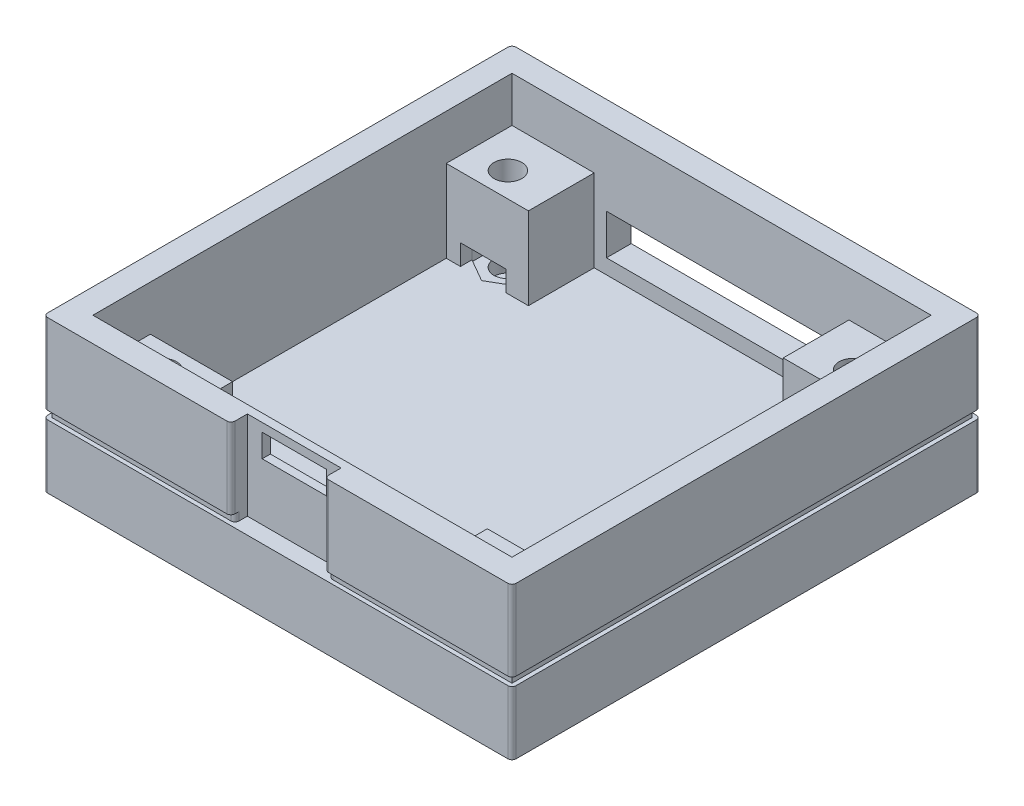
SolidWorks part; units mm, degrees
ref_plane "Plan de face" through (0, 0, 0) normal (0, 0, 1) x (1, 0, 0)
ref_plane "Plan de dessus" through (0, 0, 0) normal (0, 1, 0) x (1, 0, 0)
ref_plane "Plan de droite" through (0, 0, 0) normal (1, 0, 0) x (0, 0, -1)
sketch "Esquisse1" plane through (0, 0, 0) normal (0, 1, 0) x (1, 0, 0)
  line L1 (-30.0101, 36.8942) -> (26.9899, 36.8942)
  line L2 (-30.0101, 36.8942) -> (-30.0101, -20.1058)
  line L3 (-30.0101, -20.1058) -> (26.9899, -20.1058)
  line L4 (26.9899, 36.8942) -> (26.9899, -20.1058)
extrude "Boss.-Extru.1" add sketch "Esquisse1" along normal blind 18.5 contours L2 L3 L4 L1
sketch "Esquisse2" plane through (0, 18.5, 0) normal (0, 1, 0) x (1, 0, 0)
  line L0 (-30.0101, 36.8942) -> (26.9899, 36.8942) construction
  line L1 (-27.0101, 33.8942) -> (23.9899, 33.8942)
  line L2 (-27.0101, 33.8942) -> (-27.0101, -17.1058)
  line L3 (-27.0101, -17.1058) -> (23.9899, -17.1058)
  line L4 (23.9899, 33.8942) -> (23.9899, -17.1058)
  line L5 (-30.0101, 36.8942) -> (-30.0101, -20.1058) construction
  line L6 (26.9899, 36.8942) -> (26.9899, -20.1058) construction
  line L7 (-30.0101, -20.1058) -> (26.9899, -20.1058) construction
  dimension "D1" = 3
  dimension "D2" = 3
  dimension "D3" = 3
  dimension "D4" = 3
extrude "Enlèv. mat.-Extru.1" cut sketch "Esquisse2" against normal blind 15.5 contours L2 L3 L4 L1
sketch "Esquisse4" plane through (0, 3, 0) normal (0, 1, 0) x (1, 0, 0)
  line L1 (-17.0101, 25.8942) -> (-27.0101, 25.8942)
  line L2 (-17.0101, 25.8942) -> (-17.0101, 33.8942)
  line L3 (-17.0101, 33.8942) -> (-27.0101, 33.8942)
  line L4 (-27.0101, 25.8942) -> (-27.0101, 33.8942)
extrude "Boss.-Extru.2" add sketch "Esquisse4" along normal blind 10
sketch "Esquisse5" plane through (0, 3, 0) normal (0, 1, 0) x (1, 0, 0)
  line L1 (23.9899, 33.8942) -> (13.9899, 33.8942)
  line L2 (23.9899, 33.8942) -> (23.9899, 25.8942)
  line L3 (23.9899, 25.8942) -> (13.9899, 25.8942)
  line L4 (13.9899, 33.8942) -> (13.9899, 25.8942)
extrude "Boss.-Extru.3" add sketch "Esquisse5" along normal blind 10
sketch "Esquisse6" plane through (0, 3, 0) normal (0, 1, 0) x (1, 0, 0)
  line L1 (23.9899, -17.1058) -> (13.9899, -17.1058)
  line L2 (23.9899, -17.1058) -> (23.9899, -10.1058)
  line L3 (23.9899, -10.1058) -> (13.9899, -10.1058)
  line L4 (13.9899, -17.1058) -> (13.9899, -10.1058)
extrude "Boss.-Extru.4" add sketch "Esquisse6" along normal blind 10
sketch "Esquisse7" plane through (0, 3, 0) normal (0, 1, 0) x (1, 0, 0)
  line L1 (-17.0101, -10.1058) -> (-27.0101, -10.1058)
  line L2 (-17.0101, -10.1058) -> (-17.0101, -17.1058)
  line L3 (-17.0101, -17.1058) -> (-27.0101, -17.1058)
  line L4 (-27.0101, -10.1058) -> (-27.0101, -17.1058)
extrude "Boss.-Extru.5" add sketch "Esquisse7" along normal blind 10
sketch "Esquisse8" plane through (0, 13, 0) normal (0, 1, 0) x (1, 0, 0)
  line L0 (13.9899, -17.1058) -> (23.9899, -17.1058) construction
  line L2 (23.9899, -17.1058) -> (23.9899, -10.1058) construction
  circle A0 centre (19.4899, -13.1058) radius 1.7
  dimension "D1" = 4
  dimension "D2" = 4.5
extrude "Enlèv. mat.-Extru.2" cut sketch "Esquisse8" against normal blind 12
sketch "Esquisse9" plane through (0, 13, 0) normal (0, 1, 0) x (1, 0, 0)
  line L0 (-27.0101, -17.1058) -> (-17.0101, -17.1058) construction
  line L1 (-27.0101, -10.1058) -> (-27.0101, -17.1058) construction
  circle A0 centre (-22.5101, -13.1058) radius 1.7
  dimension "D1" = 4
  dimension "D2" = 4.5
extrude "Enlèv. mat.-Extru.3" cut sketch "Esquisse9" against normal blind 12
sketch "Esquisse16" plane through (0, 13, 0) normal (0, 1, 0) x (1, 0, 0)
  line L0 (-17.0101, 33.8942) -> (-27.0101, 33.8942) construction
  line L1 (-27.0101, 33.8942) -> (-27.0101, 25.8942) construction
  circle A0 centre (-22.5101, 28.8942) radius 1.7
  dimension "D1" = 5
  dimension "D2" = 4.5
extrude "Enlèv. mat.-Extru.9" cut sketch "Esquisse16" against normal blind 12 contours A0
sketch "Esquisse17" plane through (0, 13, 0) normal (0, 1, 0) x (1, 0, 0)
  line L0 (23.9899, 33.8942) -> (13.9899, 33.8942) construction
  line L1 (23.9899, 25.8942) -> (23.9899, 33.8942) construction
  circle A0 centre (19.4899, 28.8942) radius 1.7
  dimension "D1" = 5
  dimension "D2" = 4.5
extrude "Enlèv. mat.-Extru.10" cut sketch "Esquisse17" against normal blind 12
sketch "Esquisse21" plane through (0, 0, 20.1058) normal (0, 0, 1) x (1, 0, 0)
  line L0 (-30.0101, 0) -> (26.9899, 0) construction
  line L1 (-5.4101, 17.47) -> (2.3899, 17.47)
  line L2 (-5.4101, 17.47) -> (-5.4101, 14.67)
  line L3 (-5.4101, 14.67) -> (2.3899, 14.67)
  line L4 (2.3899, 17.47) -> (2.3899, 14.67)
  line L5 (-30.0101, 18.5) -> (-30.0101, 0) construction
  line L7 (26.9899, 18.5) -> (26.9899, 0) construction
  dimension "D1" = 14.67
  dimension "D2" = 24.6
  dimension "D3" = 24.6
extrude "Enlèv. mat.-Extru.14" cut sketch "Esquisse21" against normal blind 3
sketch "Esquisse23" plane through (0, 0, -25.8942) normal (0, 0, 1) x (1, 0, 0)
  line L0 (13.9899, 13) -> (13.9899, 3) construction
  line L5 (22.2599, 5.5) -> (16.7199, 5.5)
  line L6 (22.2599, 5.5) -> (22.2599, 3)
  line L7 (22.2599, 3) -> (16.7199, 3)
  line L8 (16.7199, 5.5) -> (16.7199, 3)
  line L9 (23.9899, 13) -> (23.9899, 3) construction
  dimension "D1" = 2.73
  dimension "D2" = 1.73
sketch "Esquisse24" plane through (0, 13, 0) normal (0, 1, 0) x (1, 0, 0)
  line L1 (19.4899, 25.6942) -> (22.2612, 27.2942)
  line L2 (22.2612, 27.2942) -> (22.2612, 30.4942)
  line L3 (22.2612, 30.4942) -> (19.4899, 32.0942)
  line L4 (19.4899, 32.0942) -> (16.7186, 30.4942)
  line L5 (16.7186, 30.4942) -> (16.7186, 27.2942)
  line L6 (16.7186, 27.2942) -> (19.4899, 25.6942)
  circle A0 centre (19.4899, 28.8942) radius 2.7713 construction
  circle A1 centre (19.4899, 28.8942) radius 1.7 construction
  dimension "D1" = 0
extrude "Enlèv. mat.-Extru.18" cut sketch "Esquisse24" against normal blind 2.7 from offset 7.5 contours L1 L2 L3 L4 L5 L6 offset against normal yes
sketch "Esquisse25" plane through (0, 13, 0) normal (0, 1, 0) x (1, 0, 0)
  line L1 (16.7186, -11.5058) -> (16.7186, -14.7058)
  line L2 (16.7186, -14.7058) -> (19.4899, -16.3058)
  line L3 (19.4899, -16.3058) -> (22.2612, -14.7058)
  line L4 (22.2612, -14.7058) -> (22.2612, -11.5058)
  line L5 (22.2612, -11.5058) -> (19.4899, -9.9058)
  line L6 (19.4899, -9.9058) -> (16.7186, -11.5058)
  circle A0 centre (19.4899, -13.1058) radius 2.7713 construction
  circle A1 centre (19.4899, -13.1058) radius 1.7 construction
  dimension "D1" = 0
extrude "Enlèv. mat.-Extru.20" cut sketch "Esquisse25" against normal blind 2.7 from offset 7.5 offset against normal yes
sketch "Esquisse26" plane through (0, 0, 10.1058) normal (0, 0, -1) x (-1, 0, 0)
  line L0 (-13.9899, 13) -> (-13.9899, 3) construction
  line L1 (-22.2599, 5.5) -> (-16.7199, 5.5)
  line L2 (-22.2599, 5.5) -> (-22.2599, 3)
  line L3 (-22.2599, 3) -> (-16.7199, 3)
  line L4 (-16.7199, 5.5) -> (-16.7199, 3)
  line L5 (-23.9899, 13) -> (-23.9899, 3) construction
  dimension "D1" = 2.73
  dimension "D2" = 1.73
extrude "Enlèv. mat.-Extru.21" cut sketch "Esquisse26" against normal blind 2.848
sketch "Esquisse27" plane through (0, 13, 0) normal (0, 1, 0) x (1, 0, 0)
  line L1 (-19.7388, 27.2942) -> (-19.7388, 30.4942)
  line L2 (-19.7388, 30.4942) -> (-22.5101, 32.0942)
  line L3 (-22.5101, 32.0942) -> (-25.2814, 30.4942)
  line L4 (-25.2814, 30.4942) -> (-25.2814, 27.2942)
  line L5 (-25.2814, 27.2942) -> (-22.5101, 25.6942)
  line L6 (-22.5101, 25.6942) -> (-19.7388, 27.2942)
  circle A0 centre (-22.5101, 28.8942) radius 2.7713 construction
  circle A1 centre (-22.5101, 28.8942) radius 1.7 construction
  dimension "D1" = 0
  dimension "D2" = 0
extrude "Enlèv. mat.-Extru.22" cut sketch "Esquisse27" against normal blind 2.7 from offset 7.5 contours L4 L5 L6 L1 L2 L3 offset against normal yes
sketch "Esquisse29" plane through (0, 13, 0) normal (0, 1, 0) x (1, 0, 0)
  line L1 (-19.7388, -11.5058) -> (-22.5101, -9.9058)
  line L2 (-22.5101, -9.9058) -> (-25.2814, -11.5058)
  line L3 (-25.2814, -11.5058) -> (-25.2814, -14.7058)
  line L4 (-25.2814, -14.7058) -> (-22.5101, -16.3058)
  line L5 (-22.5101, -16.3058) -> (-19.7388, -14.7058)
  line L6 (-19.7388, -14.7058) -> (-19.7388, -11.5058)
  circle A0 centre (-22.5101, -13.1058) radius 2.7713 construction
  circle A1 centre (-22.5101, -13.1058) radius 1.7 construction
  dimension "D1" = 0
extrude "Enlèv. mat.-Extru.24" cut sketch "Esquisse29" against normal blind 2.7 from offset 7.5 offset against normal yes
sketch "Esquisse30" plane through (0, 0, 10.1058) normal (0, 0, -1) x (-1, 0, 0)
  line L0 (17.0101, 13) -> (17.0101, 3) construction
  line L1 (25.2801, 5.5) -> (19.7401, 5.5)
  line L2 (25.2801, 5.5) -> (25.2801, 3)
  line L3 (25.2801, 3) -> (19.7401, 3)
  line L4 (19.7401, 5.5) -> (19.7401, 3)
  line L5 (27.0101, 13) -> (27.0101, 3) construction
  dimension "D1" = 2.73
  dimension "D2" = 1.73
extrude "Enlèv. mat.-Extru.26" cut sketch "Esquisse23" against normal blind 2 contours L5 L8 L7 L6
sketch "Esquisse31" plane through (0, 0, -25.8942) normal (0, 0, 1) x (1, 0, 0)
  line L0 (-27.0101, 13) -> (-27.0101, 3) construction
  line L1 (-25.2801, 5.5) -> (-19.7401, 5.5)
  line L2 (-25.2801, 5.5) -> (-25.2801, 3)
  line L3 (-25.2801, 3) -> (-19.7401, 3)
  line L4 (-19.7401, 5.5) -> (-19.7401, 3)
  line L6 (-17.0101, 13) -> (-17.0101, 3) construction
  dimension "D1" = 1.73
  dimension "D2" = 2.73
extrude "Enlèv. mat.-Extru.27" cut sketch "Esquisse31" against normal blind 2 contours L1 L4 L3 L2
extrude "Enlèv. mat.-Extru.28" cut sketch "Esquisse30" against normal blind 2 contours L1 L4 L3 L2
sketch "Esquisse32" plane through (-30.0101, 0, 0) normal (-1, 0, 0) x (0, 0, 1)
  line L0 (20.1058, 18.5) -> (20.1058, 0) construction
  line L1 (20.1058, 8.72) -> (-36.8942, 8.72)
  line L2 (20.1058, 8.72) -> (20.1058, 7.72)
  line L3 (20.1058, 7.72) -> (-36.8942, 7.72)
  line L4 (-36.8942, 8.72) -> (-36.8942, 7.72)
  line L5 (-36.8942, 18.5) -> (-36.8942, 0) construction
sketch "Esquisse33" plane through (0, 0, 20.1058) normal (0, 0, 1) x (1, 0, 0)
  line L0 (26.9899, 18.5) -> (26.9899, 0) construction
  line L1 (-30.0101, 8.72) -> (26.9899, 8.72)
  line L2 (-30.0101, 8.72) -> (-30.0101, 7.72)
  line L3 (-30.0101, 7.72) -> (26.9899, 7.72)
  line L4 (26.9899, 8.72) -> (26.9899, 7.72)
extrude "Enlèv. mat.-Extru.29" cut sketch "Esquisse32" against normal blind 0.5
extrude "Enlèv. mat.-Extru.30" cut sketch "Esquisse33" against normal blind 0.5 contours L1 L4 L3 L2
sketch "Esquisse34" plane through (26.9899, 0, 0) normal (1, 0, 0) x (0, 0, -1)
  line L0 (36.8942, 18.5) -> (36.8942, 0) construction
  line L1 (-20.1058, 7.72) -> (36.8942, 7.72)
  line L2 (-20.1058, 7.72) -> (-20.1058, 8.72)
  line L3 (-20.1058, 8.72) -> (36.8942, 8.72)
  line L4 (36.8942, 7.72) -> (36.8942, 8.72)
extrude "Enlèv. mat.-Extru.31" cut sketch "Esquisse34" against normal blind 0.5
sketch "Esquisse35" plane through (0, 0, -36.8942) normal (0, 0, -1) x (-1, 0, 0)
  line L0 (29.5101, 8.72) -> (30.0101, 8.72) construction
  line L1 (-26.9899, 7.72) -> (30.0101, 7.72)
  line L2 (-26.9899, 7.72) -> (-26.9899, 8.72)
  line L3 (-26.9899, 8.72) -> (30.0101, 8.72)
  line L4 (30.0101, 7.72) -> (30.0101, 8.72)
  line L5 (30.0101, 18.5) -> (30.0101, 8.72) construction
extrude "Enlèv. mat.-Extru.32" cut sketch "Esquisse35" against normal blind 0.5
sketch "Esquisse36" plane through (0, 0, 20.1058) normal (0, 0, 1) x (1, 0, 0)
  line L0 (-30.0101, 18.5) -> (26.9899, 18.5) construction
  line L1 (4.1899, 7.72) -> (-7.2101, 7.72)
  line L2 (4.1899, 7.72) -> (4.1899, 18.5)
  line L3 (4.1899, 18.5) -> (-7.2101, 18.5)
  line L4 (-7.2101, 7.72) -> (-7.2101, 18.5)
  line L6 (2.3899, 14.67) -> (2.3899, 17.47) construction
  line L7 (-5.4101, 17.47) -> (-5.4101, 14.67) construction
  line L9 (26.9899, 7.72) -> (-30.0101, 7.72) construction
  dimension "D1" = 1.8
  dimension "D2" = 1.8
extrude "Enlèv. mat.-Extru.33" cut sketch "Esquisse36" against normal blind 2
fillet "Congé1" radius 0.5 1 edges at (-7.2101, 13.61, 20.1058)
fillet "Congé2" radius 0.5 1 edges at (4.1899, 13.61, 20.1058)
fillet "Congé3" radius 0.5 1 edges at (-7.2101, 8.22, 19.6058)
fillet "Congé4" radius 0.5 1 edges at (4.1899, 8.22, 19.6058)
fillet "Congé5" radius 0.5 1 edges at (26.9899, 13.61, 20.1058)
fillet "Congé6" radius 0.5 1 edges at (26.9899, 3.86, 20.1058)
fillet "Congé7" radius 0.5 1 edges at (26.9899, 13.61, -36.8942)
fillet "Congé8" radius 0.5 1 edges at (26.9899, 3.86, -36.8942)
fillet "Congé9" radius 0.5 1 edges at (-30.0101, 13.61, -36.8942)
fillet "Congé10" radius 0.5 1 edges at (-30.0101, 3.86, -36.8942)
fillet "Congé11" radius 0.5 1 edges at (-30.0101, 13.61, 20.1058)
fillet "Congé12" radius 0.5 1 edges at (-30.0101, 3.86, 20.1058)
sketch "Esquisse38" plane through (0, 0, -36.8942) normal (0, 0, -1) x (-1, 0, 0)
  line L1 (-12.4899, 9.7115) -> (15.5101, 9.7115)
  line L2 (-12.4899, 9.7115) -> (-12.4899, 4.7985)
  line L3 (-12.4899, 4.7985) -> (15.5101, 4.7985)
  line L4 (15.5101, 9.7115) -> (15.5101, 4.7985)
  dimension "D1" = 5.3
  dimension "D2" = 5.3
extrude "Enlèv. mat.-Extru.34" cut sketch "Esquisse38" against normal blind 3
